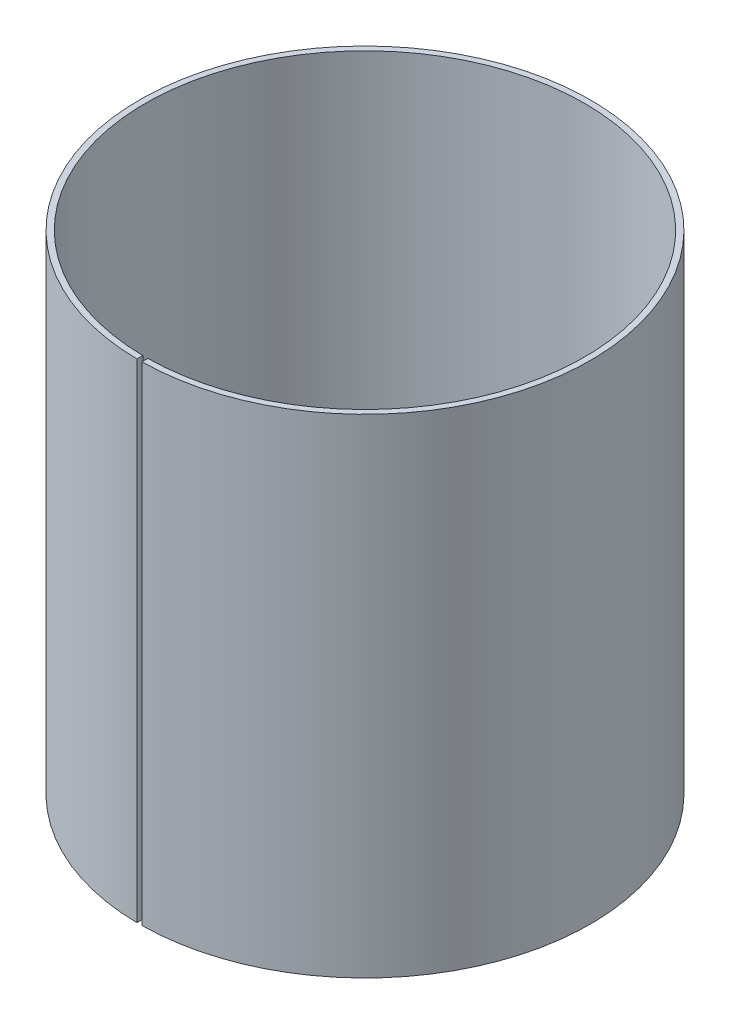
SolidWorks part; units mm, degrees
ref_plane "Спереди" through (0, 0, 0) normal (0, 0, 1) x (1, 0, 0)
ref_plane "Сверху" through (0, 0, 0) normal (0, 1, 0) x (1, 0, 0)
ref_plane "Справа" through (0, 0, 0) normal (1, 0, 0) x (0, 0, -1)
other "Configuration Table"
sketch "Эскиз1" plane through (0, 0, 0) normal (0, 1, 0) x (1, 0, 0)
  circle A0 centre (0, 0) radius 46.2
  circle A1 centre (0, 0) radius 45
  dimension "D1" = 90
  dimension "D2" = 1.2
extrude "Бобышка-Вытянуть1" add sketch "Эскиз1" along normal blind 100
sketch "Эскиз2" plane through (0, 0, 0) normal (0, 0, 1) x (1, 0, 0)
  line L0 (0, 0) -> (0, 100) construction
  line L1 (45, 100) -> (-45, 100) construction
  line L2 (0.5, 0) -> (0.5, 100)
  line L3 (-46.2, 0) -> (46.2, 0) construction
  line L4 (0.5, 100) -> (-0.5, 100)
  line L5 (46.2, 100) -> (-46.2, 100) construction
  line L6 (-0.5, 100) -> (-0.5, 0)
  line L7 (-0.5, 0) -> (0.5, 0)
  dimension "D1" = 1
  dimension "D2" = 0.5
extrude "Вырез-Вытянуть1" cut sketch "Эскиз2" along normal blind 93
